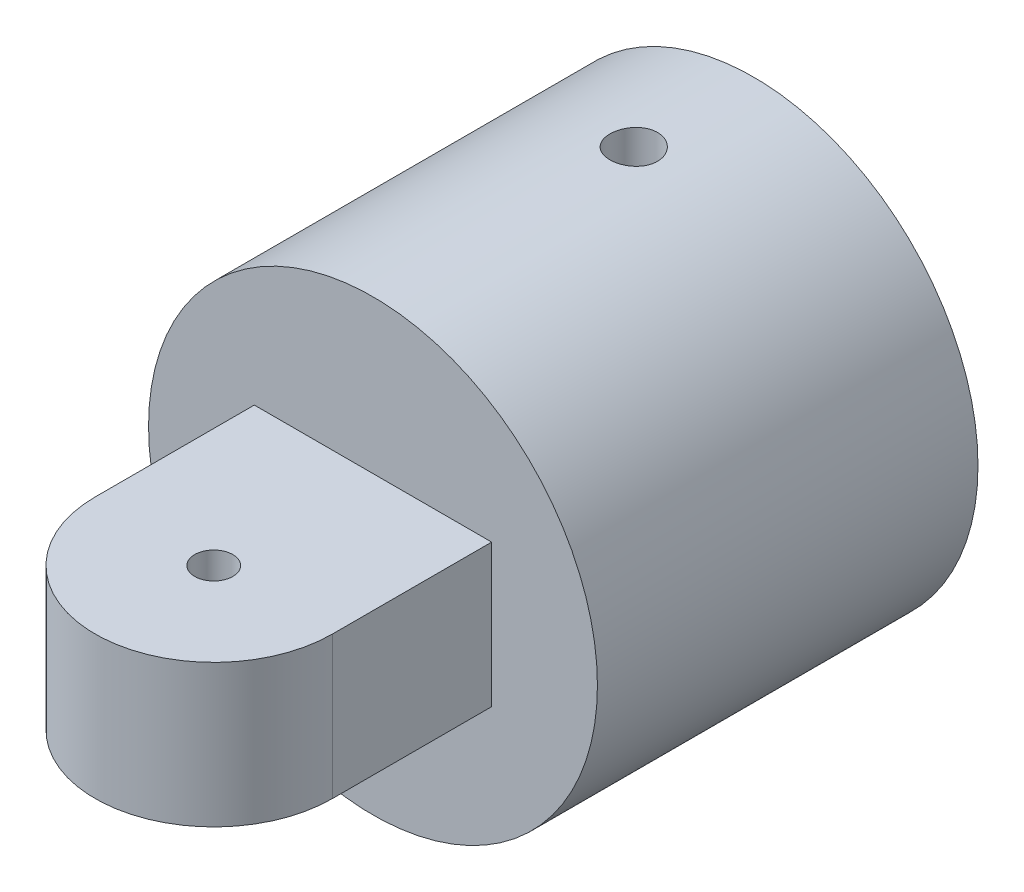
SolidWorks part; units mm, degrees
ref_plane "Plano frontal" through (0, 0, 0) normal (0, 0, 1) x (1, 0, 0)
ref_plane "Plano superior" through (0, 0, 0) normal (0, 1, 0) x (1, 0, 0)
ref_plane "Plano direito" through (0, 0, 0) normal (1, 0, 0) x (0, 0, -1)
sketch "Esboço1" plane through (0, 0, 0) normal (0, 0, 1) x (1, 0, 0)
  circle A0 centre (0, 0) radius 23.59
extrude "Ressalto-extrusão1" add sketch "Esboço1" along normal blind 30 and the other way blind 10
sketch "Esboço2" plane through (0, 0, 0) normal (0, 1, 0) x (1, 0, 0)
  line L0 (-12.4735, -30) -> (12.4735, -30)
  line L1 (-23.59, -30) -> (23.59, -30) construction
  line L2 (-12.4735, -30) -> (-12.4735, -46.7347)
  line L4 (12.4735, -46.7347) -> (12.4735, -30)
  arc A0 (-12.4735, -46.7347) -> (12.4735, -46.7347) centre (0, -46.7347) ccw
  point P5 (0, -30)
extrude "Ressalto-extrusão2" add sketch "Esboço2" along normal mid plane 14.98 separate body
sketch "Esboço3" plane through (0, 7.49, 0) normal (0, 1, 0) x (1, 0, 0)
  circle A0 centre (0, -46.7347) radius 2
extrude "Corte-extrusão1" cut sketch "Esboço3" against normal mid plane 75
ref_plane "Plano1" through (-22.4735, 0, 0) normal (-1, 0, 0) x (0, 0, 1)
sketch "Esboço4" plane through (-22.4735, 0, 0) normal (-1, 0, 0) x (0, 0, 1)
  circle A0 centre (2.5927, 0) radius 2.5
sketch "Sketch1" plane through (0, 0, 0) normal (0, 1, 0) x (1, 0, 0)
  circle A0 centre (0, -2.5927) radius 2.5
extrude "Cut-Extrude1" cut sketch "Sketch1" against normal through all both and the other way through all
